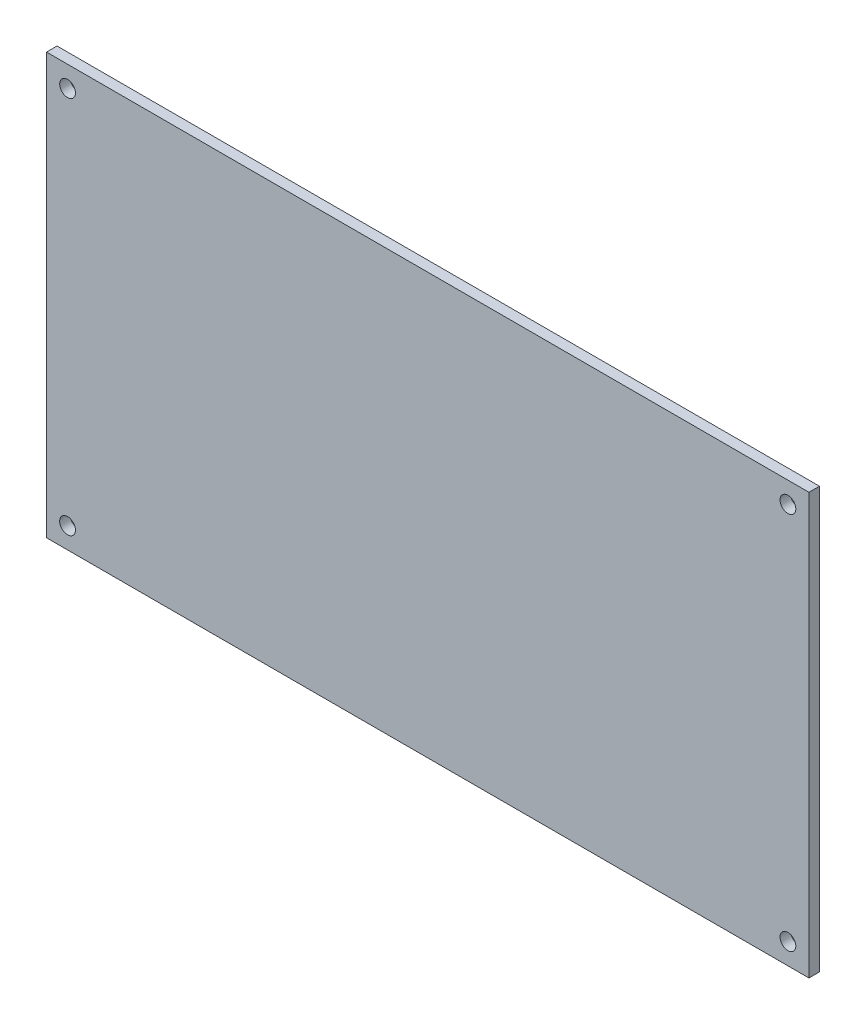
SolidWorks part; units mm, degrees
ref_plane "Спереди" through (0, 0, 0) normal (0, 0, 1) x (1, 0, 0)
ref_plane "Сверху" through (0, 0, 0) normal (0, 1, 0) x (1, 0, 0)
ref_plane "Справа" through (0, 0, 0) normal (1, 0, 0) x (0, 0, -1)
sketch "Эскиз1" plane through (0, 0, 0) normal (0, 0, 1) x (1, 0, 0)
  line L1 (0, 80) -> (145, 80)
  line L2 (0, 80) -> (0, 0)
  line L3 (0, 0) -> (145, 0)
  line L4 (145, 80) -> (145, 0)
  dimension "D1" = 80
  dimension "D2" = 145
extrude "Бобышка-Вытянуть1" add sketch "Эскиз1" along normal blind 2
sketch "Эскиз2" plane through (0, 0, 2) normal (0, 0, 1) x (1, 0, 0)
  line L0 (145, 80) -> (0, 80) construction
  line L1 (0, 80) -> (0, 0) construction
  circle A0 centre (4, 76) radius 1.5
  point P4 (0, 0)
  point P6 (7.3525, 74.9635)
  dimension "D1" = 3
  dimension "D2" = 4
  dimension "D3" = 4
extrude "Вырез-Вытянуть1" cut sketch "Эскиз2" against normal blind 2
pattern_linear "Линейный массив1" count 2 spacing 137 along (1, 0, 0) count 2 spacing 72 along (0, -1, 0) of "Вырез-Вытянуть1"
